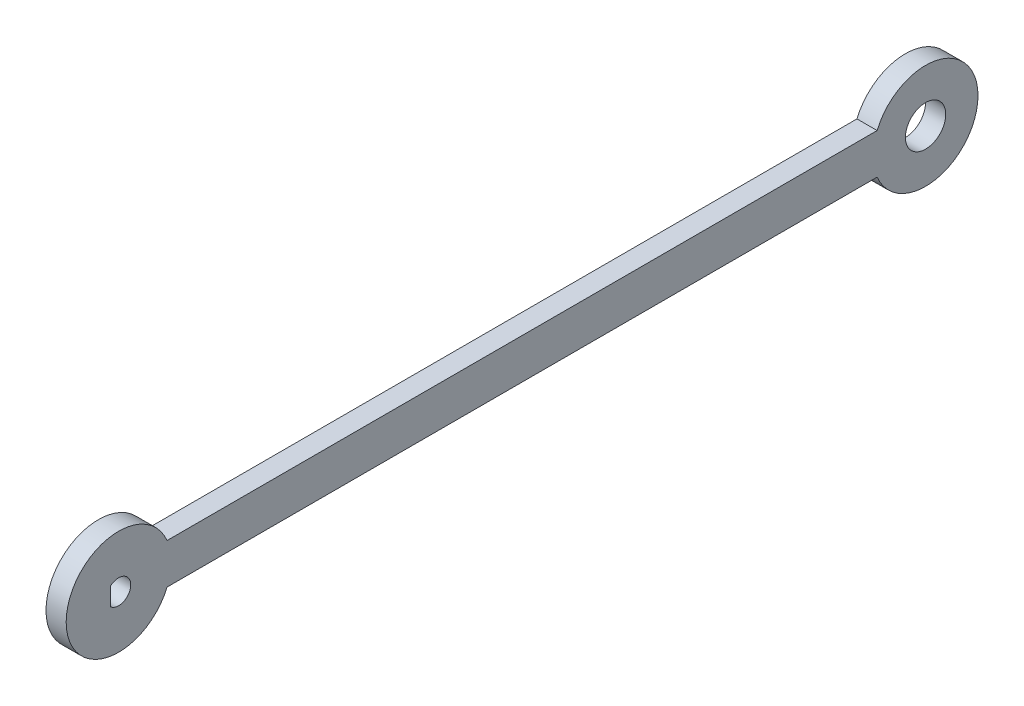
SolidWorks part; units mm, degrees
material "CA"
ref_plane "Alzado" through (0, 0, 0) normal (0, 0, 1) x (1, 0, 0)
ref_plane "Planta" through (0, 0, 0) normal (0, 1, 0) x (1, 0, 0)
ref_plane "Vista lateral" through (0, 0, 0) normal (1, 0, 0) x (0, 0, -1)
sketch "Croquis1" plane through (0, 0, 0) normal (1, 0, 0) x (0, 0, -1)
  line L0 (195, 0) -> (188, 0) construction
  line L1 (188, -5) -> (12, -5)
  line L2 (-2, 0) -> (-2, 2.2361)
  line L3 (-2, 0) -> (-2, -2.2361)
  line L5 (188, 5) -> (12, 5)
  arc A0 (12, 5) -> (12, -5) centre (0, 0) ccw
  arc A1 (-2, -2.2361) -> (-2, 2.2361) centre (0, 0) ccw
  arc A2 (188, -5) -> (188, 5) centre (200, 0) ccw
  circle A3 centre (200, 0) radius 5
  dimension "D1" = 26
  dimension "D2" = 26
  dimension "D3" = 6
  dimension "D4" = 10
  dimension "D5" = 200
  dimension "D6" = 2
extrude "Saliente-Extruir1" add sketch "Croquis1" along normal blind 5
